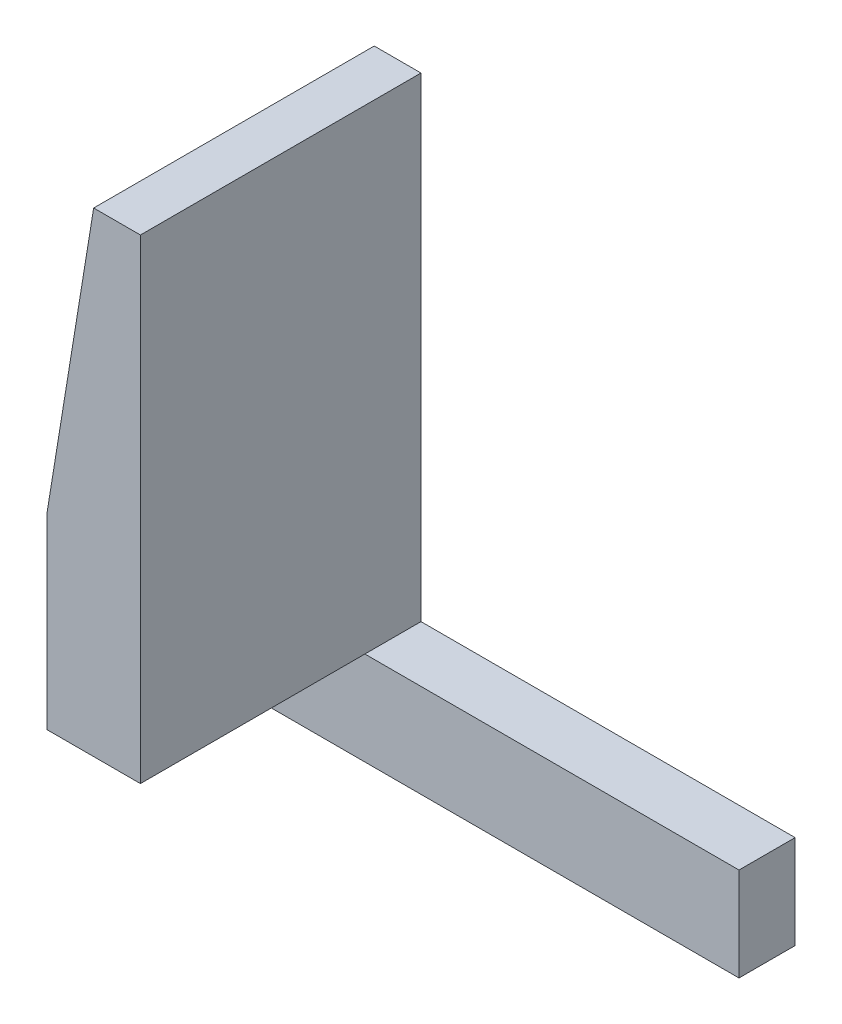
SolidWorks part; units mm, degrees
ref_plane "Front Plane" through (0, 0, 0) normal (0, 0, 1) x (1, 0, 0)
ref_plane "Top Plane" through (0, 0, 0) normal (0, 1, 0) x (1, 0, 0)
ref_plane "Right Plane" through (0, 0, 0) normal (1, 0, 0) x (0, 0, -1)
sketch "Sketch2" plane through (0, 0, 0) normal (0, 0, 1) x (1, 0, 0)
  line L0 (0, 0) -> (0, 25.4)
  line L1 (0, 25.4) -> (-2.5, 25.4)
  line L2 (-2.5, 25.4) -> (-5, 10)
  line L3 (-5, 10) -> (-5, 0)
  line L4 (-5, 0) -> (0, 0)
  point P7 (-2.5, 0)
  dimension "D1" = 25.4
  dimension "D2" = 5
  dimension "D3" = 10
extrude "Boss-Extrude1" add sketch "Sketch2" along normal blind 15
sketch "Sketch3" plane through (0, 0, 0) normal (0, -1, 0) x (1, 0, 0)
  line L0 (-5, 0) -> (20, 0)
  line L1 (20, 0) -> (20, 3)
  line L2 (-5, 0) -> (-5, 3)
  line L3 (-5, 15) -> (-5, 0) construction
  line L5 (-5, 3) -> (20, 3)
  dimension "D1" = 25
  dimension "D2" = 3
extrude "Boss-Extrude2" add sketch "Sketch3" along normal blind 5
